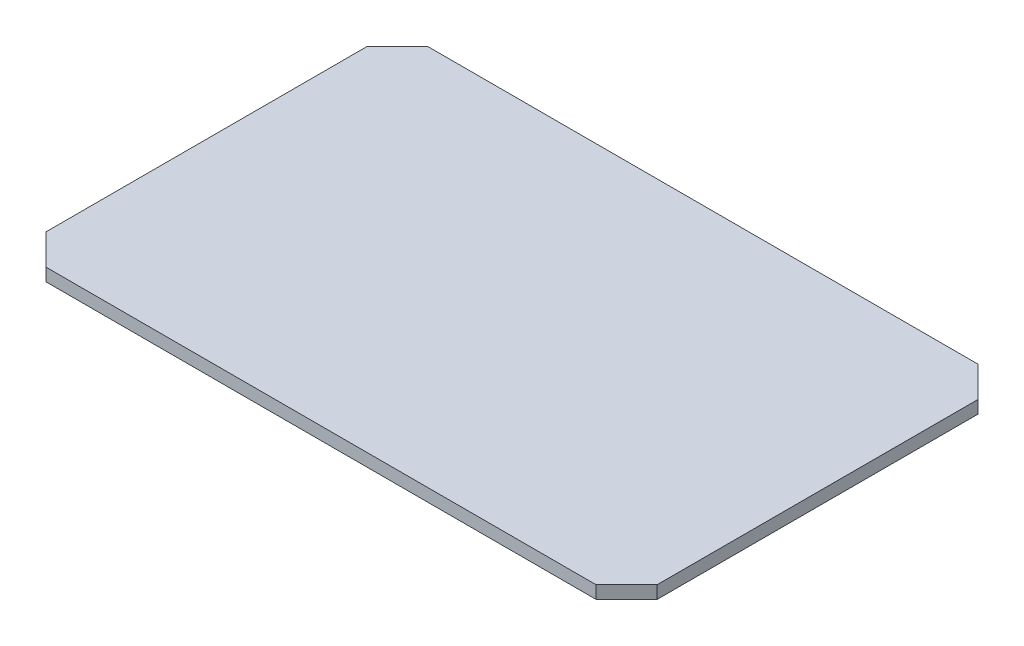
SolidWorks part; units mm, degrees
ref_plane "Plano frontal" through (0, 0, 0) normal (0, 0, 1) x (1, 0, 0)
ref_plane "Plano superior" through (0, 0, 0) normal (0, 1, 0) x (1, 0, 0)
ref_plane "Plano direito" through (0, 0, 0) normal (1, 0, 0) x (0, 0, -1)
sketch "Esboço1" plane through (0, 0, 0) normal (0, 1, 0) x (1, 0, 0)
  line L0 (2.4, 1.5) -> (-2.4, -1.5) construction
  line L1 (-2.4, 1.5) -> (2.4, 1.5)
  line L2 (-2.4, 1.5) -> (-2.4, -1.5)
  line L3 (-2.4, -1.5) -> (2.4, -1.5)
  line L4 (2.4, 1.5) -> (2.4, -1.5)
  dimension "D1" = 4.8
  dimension "D2" = 3
extrude "Extrusão1" add sketch "Esboço1" along normal blind 0.1
chamfer "Chanfro1" distance 0.24 angle 45 1 edges at (2.4, 0.05, 1.5)
chamfer "Chanfro2" distance 0.24 angle 45 1 edges at (-2.4, 0.05, 1.5)
chamfer "Chanfro3" distance 0.24 angle 45 1 edges at (2.4, 0.05, -1.5)
chamfer "Chanfro4" distance 0.24 angle 45 1 edges at (-2.4, 0.05, -1.5)
